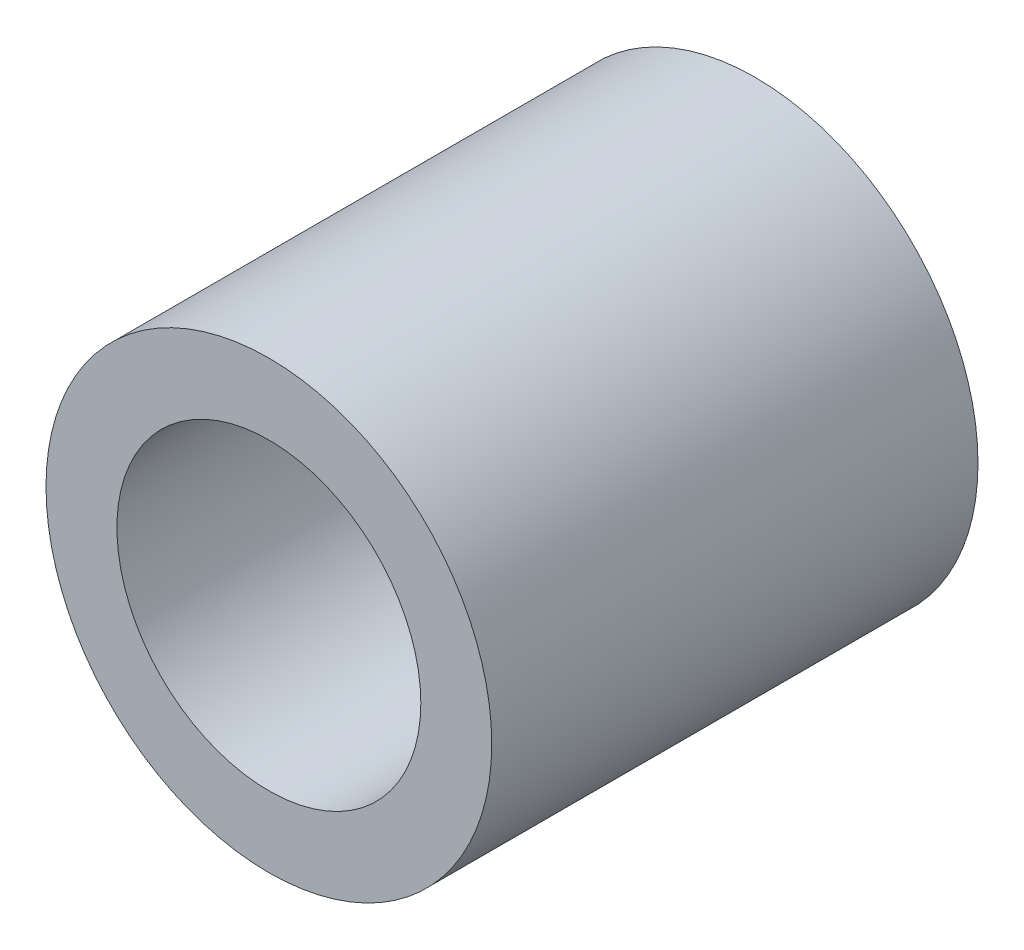
SolidWorks part; units mm, degrees
ref_plane "Front Plane" through (0, 0, 0) normal (0, 0, 1) x (1, 0, 0)
ref_plane "Top Plane" through (0, 0, 0) normal (0, 1, 0) x (1, 0, 0)
ref_plane "Right Plane" through (0, 0, 0) normal (1, 0, 0) x (0, 0, -1)
sketch "Sketch1" plane through (0, 0, 0) normal (0, 0, 1) x (1, 0, 0)
  circle A0 centre (0, 0) radius 7.5
  circle A1 centre (0, 0) radius 11
  dimension "D1" = 22
  dimension "D2" = 15
extrude "Boss-Extrude1" add sketch "Sketch1" along normal blind 24
